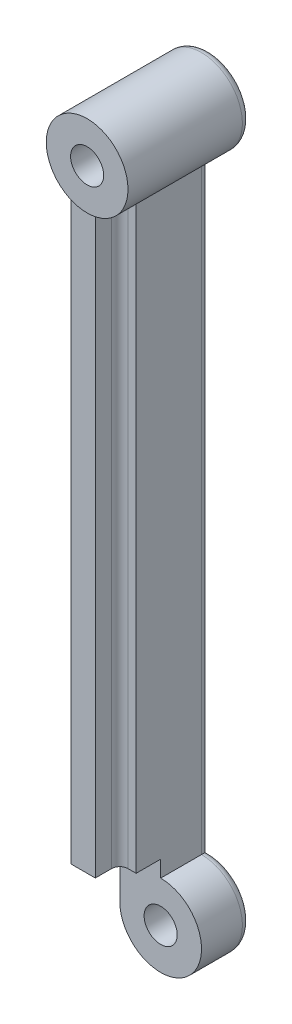
SolidWorks part; units mm, degrees
ref_plane "Front Plane" through (0, 0, 0) normal (0, 0, 1) x (1, 0, 0)
ref_plane "Top Plane" through (0, 0, 0) normal (0, 1, 0) x (1, 0, 0)
ref_plane "Right Plane" through (0, 0, 0) normal (1, 0, 0) x (0, 0, -1)
sketch "Sketch1" plane through (0, 0, 0) normal (0, 0, 1) x (1, 0, 0)
  line L0 (0, 0) -> (0, 85) construction
  line L1 (-5, 0) -> (-5, 85)
  line L3 (0, 5) -> (0, 80)
  arc A1 (0, 80) -> (-5, 85) centre (0, 85) ccw
  circle A2 centre (0, 85) radius 2.025
  circle A3 centre (0, 0) radius 2.025
  arc A4 (0, -5) -> (0, 5) centre (0, 0) ccw
  arc A5 (-5, 0) -> (0, -5) centre (0, 0) ccw
  point P3 (0, 30)
  dimension "D1" = 4.05
  dimension "D3" = 5
  dimension "D4" = 5
  dimension "D2" = 85
extrude "Boss-Extrude1" add sketch "Sketch1" along normal blind 9
sketch "Sketch2" plane through (0, 0, 9) normal (0, 0, 1) x (1, 0, 0)
  circle A0 centre (0, 85) radius 5
  circle A1 centre (0, 85) radius 2.025
  dimension "D1" = 4.05
  dimension "D2" = 10
extrude "Boss-Extrude2" add sketch "Sketch2" along normal blind 6
sketch "Sketch3" plane through (0, 0, 9) normal (0, 0, 1) x (1, 0, 0)
  line L1 (-5, 0) -> (-5, 85)
  line L3 (-2, 80.4174) -> (-2, 5)
  line L4 (-5, 85) -> (-5, 0) construction
  line L6 (-2, 5) -> (0, 5)
  line L7 (0, 5) -> (0, 80) construction
  arc A3 (-5, 0) -> (0, -5) centre (0, 0) ccw
  arc A4 (-5, 0) -> (0, 5) centre (0, 0) ccw construction
  circle A7 centre (0, 0) radius 2.025
  arc A8 (0, 5) -> (0, -5) centre (0, 0) cw
  arc A9 (-5, 0) -> (0, 5) centre (0, 0) ccw construction
  arc A10 (-5, 85) -> (-2, 80.4174) centre (0, 85) ccw
  circle A11 centre (0, 85) radius 5 construction
  dimension "D1" = 3
  dimension "D2" = 4.05
extrude "Boss-Extrude3" add sketch "Sketch3" along normal blind 3
sketch "Sketch4" plane through (0, 0, 0) normal (0, 0, -1) x (-1, 0, 0)
  line L1 (0.2377, 81.8335) -> (2.8611, 83.6226)
  line L2 (2.8611, 83.6226) -> (2.6234, 86.7891)
  line L3 (2.6234, 86.7891) -> (-0.2377, 88.1665)
  line L4 (-0.2377, 88.1665) -> (-2.8611, 86.3774)
  line L5 (-2.8611, 86.3774) -> (-2.6234, 83.2109)
  line L6 (-2.6234, 83.2109) -> (0.2377, 81.8335)
  circle A0 centre (0, 85) radius 2.75 construction
sketch "Croquis1" plane through (-5, 0, 0) normal (-1, 0, 0) x (0, 0, 1)
  line L0 (12, 85) -> (12, 0) construction
  line L1 (12, 7.0113) -> (6, 7.0113)
  line L2 (12, 7.0113) -> (12, -5)
  line L3 (12, -5) -> (6, -5)
  line L4 (6, 7.0113) -> (6, -5)
  dimension "D1" = 6
extrude "Cortar-Extruir3" cut sketch "Croquis1" against normal blind 10
fillet "Redondeo1" radius 1 4 edges at (0, 42.5, 0) (3.5355, 88.5355, 0) (3.5355, -3.5355, 0) (-5, 42.5, 0)
fillet "Redondeo2" radius 1 1 edges at (-2, 43.7143, 9)
